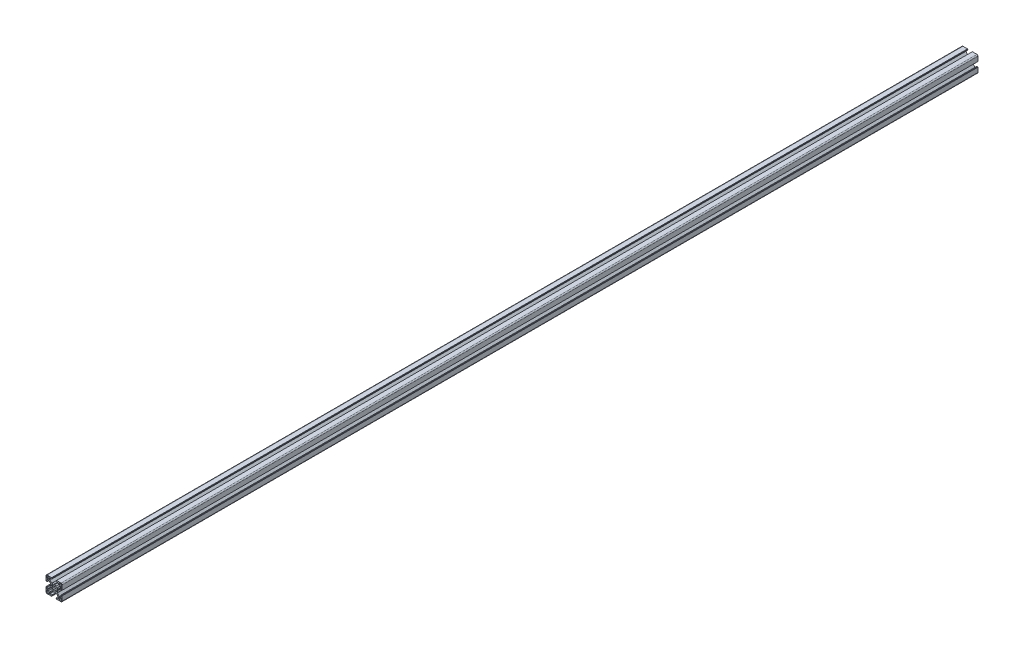
SolidWorks part; units mm, degrees
ref_plane "Front Plane" through (0, 0, 0) normal (0, 0, 1) x (1, 0, 0)
ref_plane "Top Plane" through (0, 0, 0) normal (0, 1, 0) x (1, 0, 0)
ref_plane "Right Plane" through (0, 0, 0) normal (1, 0, 0) x (0, 0, -1)
sketch "Sketch1" plane through (0, 0, 0) normal (0, 0, 1) x (1, 0, 0)
  line L0 (-15, 0) -> (15, 0) construction
  line L1 (0, -15) -> (0, 15) construction
  line L2 (-4.5, 15) -> (4.5, 15) construction
  line L3 (-4, -15) -> (4, -15) construction
  line L4 (-4.5, 15) -> (-4.5, 14.5)
  line L5 (-4.5, 14.5) -> (-4, 14.5)
  line L6 (-4, 14.5) -> (-4, 13.29)
  line L7 (-4.5, 12.79) -> (-7.7675, 12.79)
  line L8 (-8.2675, 12.29) -> (-8.2675, 10.2707)
  line L9 (-8.1211, 9.9171) -> (-4.3504, 6.1464)
  line L10 (-3.9968, 6) -> (0, 6)
  line L11 (0, 0) -> (-15, 15) construction
  line L12 (-4.5, 15) -> (-12.968, 15)
  line L14 (-12.705, 9.5135) -> (-10.5135, 9.5135)
  line L15 (-13.705, 10.5135) -> (-13.705, 12.705)
  line L16 (-12.705, 13.705) -> (-10.5135, 13.705)
  line L17 (-9.5135, 10.5135) -> (-9.5135, 12.705)
  line L18 (-13.705, 9.5135) -> (-9.5135, 13.705) construction
  line L19 (-13.705, 13.705) -> (-9.5135, 9.5135) construction
  line L20 (-3.1568, 4.5038) -> (-1.5303, 3.1477) construction
  line L21 (-4.5038, 3.1568) -> (-3.1477, 1.5303) construction
  line L22 (-6, 3.9968) -> (-6, 0)
  line L23 (-9.9171, 8.1211) -> (-6.1464, 4.3504)
  line L24 (-15, 4.5) -> (-15, 12.968)
  line L25 (-12.29, 8.2675) -> (-10.2707, 8.2675)
  line L26 (-12.79, 4.5) -> (-12.79, 7.7675)
  line L27 (-14.5, 4) -> (-13.29, 4)
  line L28 (-14.5, 4.5) -> (-14.5, 4)
  line L29 (-15, 4.5) -> (-14.5, 4.5)
  circle A0 centre (0, 0) radius 3.5
  arc A1 (-12.968, 15) -> (-15, 12.968) centre (-12.968, 12.968) ccw
  circle A2 centre (0, 0) radius 5.5 construction
  arc A3 (-10.5135, 9.5135) -> (-9.5135, 10.5135) centre (-10.5135, 10.5135) ccw
  arc A4 (-13.705, 12.705) -> (-12.705, 13.705) centre (-12.705, 12.705) cw
  arc A5 (-10.5135, 13.705) -> (-9.5135, 12.705) centre (-10.5135, 12.705) cw
  arc A6 (-12.705, 9.5135) -> (-13.705, 10.5135) centre (-12.705, 10.5135) cw
  arc A7 (-12.79, 4.5) -> (-13.29, 4) centre (-13.29, 4.5) cw
  arc A8 (-12.29, 8.2675) -> (-12.79, 7.7675) centre (-12.29, 7.7675) ccw
  arc A9 (-9.9171, 8.1211) -> (-10.2707, 8.2675) centre (-10.2707, 7.7675) ccw
  arc A10 (-6, 3.9968) -> (-6.1464, 4.3504) centre (-6.5, 3.9968) ccw
  arc A11 (-4.3504, 6.1464) -> (-3.9968, 6) centre (-3.9968, 6.5) ccw
  arc A12 (-4, 13.29) -> (-4.5, 12.79) centre (-4.5, 13.29) cw
  arc A13 (-7.7675, 12.79) -> (-8.2675, 12.29) centre (-7.7675, 12.29) ccw
  arc A14 (-8.2675, 10.2707) -> (-8.1211, 9.9171) centre (-7.7675, 10.2707) ccw
  point P4 (0, 0)
  point P8 (0, 0)
  point P13 (0, 15)
  point P15 (0, -15)
  point P16 (0, 6)
  point P23 (-11.6092, 11.6093)
  point P26 (0, 6)
  point P62 (-12.79, 4)
  point P65 (-12.79, 8.2675)
  point P68 (-10.0636, 8.2675)
  point P71 (-6, 4.2039)
  point P74 (-4.2039, 6)
  point P77 (-4, 12.79)
  point P80 (-8.2675, 12.79)
  point P83 (-8.2675, 10.0636)
  dimension "Center Hole Diameter" = 7
  dimension "D11" = 2.032
  dimension "D9" = 11
  dimension "D13" = 1
  dimension "D14" = 0.5
  dimension "Rail Height" = 30
  dimension "Rail Width" = 30
  dimension "T-Slot Width" = 8
  dimension "T-Slot Depth" = 9
  dimension "D1" = 9
  dimension "D2" = 45
  dimension "D3" = 8
  dimension "D4" = 2.21
  dimension "D5" = 16.535
  dimension "D7" = 2.54
  dimension "D6" = 1.295
  dimension "D8" = 1.246
  dimension "D10" = 10.36
  dimension "D12" = 1.905
sketch "Sketch2" plane through (0, 0, 0) normal (1, 0, 0) x (0, 0, -1)
  line L0 (-76.2, 0) -> (76.2, 0) construction
  line L2 (0, -15) -> (0, 15) construction
  line L3 (0, -15) -> (0, 15) construction
  line L4 (-76.2, -15) -> (-76.2, 15) construction
  line L5 (76.2, -15) -> (76.2, 15) construction
  point P0 (-38.7, 0)
  point P3 (0, 0)
  point P4 (38.7, 0)
  point P12 (-76.2, 0)
  point P14 (76.2, 0)
  dimension "Length" = 152.4
  dimension "D1" = 37.5
sketch "Sketch3" plane through (0, 0, 0) normal (0, 0, 1) x (1, 0, 0)
  line L0 (-4.5038, 3.1568) -> (-3.1477, 1.5303)
  line L1 (0, 3.5) -> (0, 5.5)
  line L2 (-5.5, 0) -> (-3.5, 0)
  line L7 (-6, 3.9968) -> (-6, 0) construction
  line L31 (-9.9171, 8.1211) -> (-6.1464, 4.3504) construction
  line L117 (-12.29, 8.2675) -> (-10.2707, 8.2675) construction
  line L118 (-12.79, 4.5) -> (-12.79, 7.7675) construction
  line L157 (-12.705, 9.5135) -> (-10.5135, 9.5135)
  line L158 (-9.5135, 10.5135) -> (-9.5135, 12.705)
  line L163 (-10.5135, 13.705) -> (-12.705, 13.705)
  line L164 (-13.705, 12.705) -> (-13.705, 10.5135)
  line L165 (-12.705, 9.5135) -> (-10.5135, 9.5135)
  line L166 (-9.5135, 10.5135) -> (-9.5135, 12.705)
  line L167 (-10.5135, 13.705) -> (-12.705, 13.705)
  line L168 (-13.705, 12.705) -> (-13.705, 10.5135)
  line L169 (-14.5, 4) -> (-13.29, 4) construction
  line L170 (-14.5, 4.5) -> (-14.5, 4) construction
  line L171 (-15, 4.5) -> (-14.5, 4.5) construction
  line L172 (-15, 4.5) -> (-15, 12.968) construction
  line L173 (-4.5, 15) -> (-12.968, 15) construction
  line L174 (-4.5, 15) -> (-4.5, 14.5) construction
  line L175 (-4.5, 14.5) -> (-4, 14.5) construction
  line L176 (-4, 14.5) -> (-4, 13.29) construction
  line L177 (-4.5, 12.79) -> (-7.7675, 12.79) construction
  line L178 (-8.2675, 12.29) -> (-8.2675, 10.2707) construction
  line L179 (-8.1211, 9.9171) -> (-4.3504, 6.1464) construction
  line L180 (-3.9968, 6) -> (0, 6) construction
  line L181 (-6, 3.9968) -> (-6, 0.866)
  line L182 (-9.9171, 8.1211) -> (-6.1464, 4.3504)
  line L183 (-12.29, 8.2675) -> (-10.2707, 8.2675)
  line L184 (-12.79, 4.5) -> (-12.79, 7.7675)
  line L185 (-14.5, 4) -> (-13.29, 4)
  line L186 (-14.5, 4.5) -> (-14.5, 4)
  line L187 (-15, 4.5) -> (-14.5, 4.5)
  line L188 (-15, 4.5) -> (-15, 12.968)
  line L189 (-4.5, 15) -> (-12.968, 15)
  line L190 (-4.5, 15) -> (-4.5, 14.5)
  line L191 (-4.5, 14.5) -> (-4, 14.5)
  line L192 (-4, 14.5) -> (-4, 13.29)
  line L193 (-4.5, 12.79) -> (-7.7675, 12.79)
  line L194 (-8.2675, 12.29) -> (-8.2675, 10.2707)
  line L195 (-8.1211, 9.9171) -> (-4.3504, 6.1464)
  line L196 (-3.9968, 6) -> (-0.866, 6)
  line L197 (-0.866, 6) -> (0, 5.5)
  line L198 (0, -15) -> (0, 15) construction
  line L199 (0, 0) -> (-15, 15) construction
  line L200 (0, 0) -> (-15, 15) construction
  line L201 (-3.1568, 4.5038) -> (-1.5303, 3.1477) construction
  line L202 (-3.1568, 4.5038) -> (-1.5303, 3.1477)
  line L203 (-6, 0.866) -> (-5.5, 0)
  line L204 (-15, 0) -> (15, 0) construction
  line L205 (-15, 0) -> (15, 0) construction
  line L206 (0, -15) -> (0, 15) construction
  arc A0 (-3.5, 0) -> (-3.1477, 1.5303) centre (0, 0) cw
  arc A10 (-6, 3.9968) -> (-6.1464, 4.3504) centre (-6.5, 3.9968) ccw construction
  circle A16 centre (0, 0) radius 3.5
  arc A18 (0, 3.5) -> (-1.5303, 3.1477) centre (0, 0) ccw
  arc A20 (-9.9171, 8.1211) -> (-10.2707, 8.2675) centre (-10.2707, 7.7675) ccw construction
  arc A22 (-12.29, 8.2675) -> (-12.79, 7.7675) centre (-12.29, 7.7675) ccw construction
  arc A28 (-13.29, 4) -> (-12.79, 4.5) centre (-13.29, 4.5) ccw construction
  arc A29 (-10.5135, 9.5135) -> (-9.5135, 10.5135) centre (-10.5135, 10.5135) ccw
  arc A30 (-9.5135, 12.705) -> (-10.5135, 13.705) centre (-10.5135, 12.705) ccw
  arc A31 (-12.705, 13.705) -> (-13.705, 12.705) centre (-12.705, 12.705) ccw
  arc A32 (-13.705, 10.5135) -> (-12.705, 9.5135) centre (-12.705, 10.5135) ccw
  arc A33 (-10.5135, 9.5135) -> (-9.5135, 10.5135) centre (-10.5135, 10.5135) ccw
  arc A34 (-9.5135, 12.705) -> (-10.5135, 13.705) centre (-10.5135, 12.705) ccw
  arc A35 (-12.705, 13.705) -> (-13.705, 12.705) centre (-12.705, 12.705) ccw
  arc A36 (-13.705, 10.5135) -> (-12.705, 9.5135) centre (-12.705, 10.5135) ccw
  arc A37 (-12.968, 15) -> (-15, 12.968) centre (-12.968, 12.968) ccw construction
  arc A38 (-4.5, 12.79) -> (-4, 13.29) centre (-4.5, 13.29) ccw construction
  arc A39 (-7.7675, 12.79) -> (-8.2675, 12.29) centre (-7.7675, 12.29) ccw construction
  arc A40 (-8.2675, 10.2707) -> (-8.1211, 9.9171) centre (-7.7675, 10.2707) ccw construction
  arc A41 (-4.3504, 6.1464) -> (-3.9968, 6) centre (-3.9968, 6.5) ccw construction
  arc A42 (-6, 3.9968) -> (-6.1464, 4.3504) centre (-6.5, 3.9968) ccw
  arc A43 (-9.9171, 8.1211) -> (-10.2707, 8.2675) centre (-10.2707, 7.7675) ccw
  arc A44 (-12.29, 8.2675) -> (-12.79, 7.7675) centre (-12.29, 7.7675) ccw
  arc A45 (-13.29, 4) -> (-12.79, 4.5) centre (-13.29, 4.5) ccw
  arc A46 (-12.968, 15) -> (-15, 12.968) centre (-12.968, 12.968) ccw
  arc A47 (-4.5, 12.79) -> (-4, 13.29) centre (-4.5, 13.29) ccw
  arc A48 (-7.7675, 12.79) -> (-8.2675, 12.29) centre (-7.7675, 12.29) ccw
  arc A49 (-8.2675, 10.2707) -> (-8.1211, 9.9171) centre (-7.7675, 10.2707) ccw
  arc A50 (-4.3504, 6.1464) -> (-3.9968, 6) centre (-3.9968, 6.5) ccw
  circle A51 centre (0, 0) radius 5.5 construction
  arc A52 (-3.1568, 4.5038) -> (-4.5038, 3.1568) centre (0, 0) ccw
  dimension "D3" = 60
  dimension "D4" = 60
  dimension "D1" = 0
  dimension "D2" = 0
extrude "Boss-Extrude1" add sketch "Sketch3" along normal mid plane 1700
pattern_circular "CirPattern1" count 4 over 360 about axis through (0, 0, 0) along (0, 0, 1) of "Boss-Extrude1"
ref_plane "Contact Plane1" through (15, 0, 0) normal (1, 0, 0) x (0, 0, -1)
ref_plane "Contact Plane2" through (0, -15, 0) normal (0, 1, 0) x (1, 0, 0)
ref_plane "Contact Plane3" through (-15, 0, 0) normal (1, 0, 0) x (0, 0, -1)
ref_plane "Contact Plane4" through (0, 15, 0) normal (0, 1, 0) x (1, 0, 0)
equation "\"D1@Sketch2\" = \"Rail Height@Sketch1\" * 1.25"
equation "\"D1@Sketch1\"=\"T-Slot Width@Sketch1\"+1mm"
equation "\"D3@Sketch1\"=\"T-Slot Width@Sketch1\""
equation "\"D1@Boss-Extrude1\"=\"length\""
equation "\"length\"= 1700"
